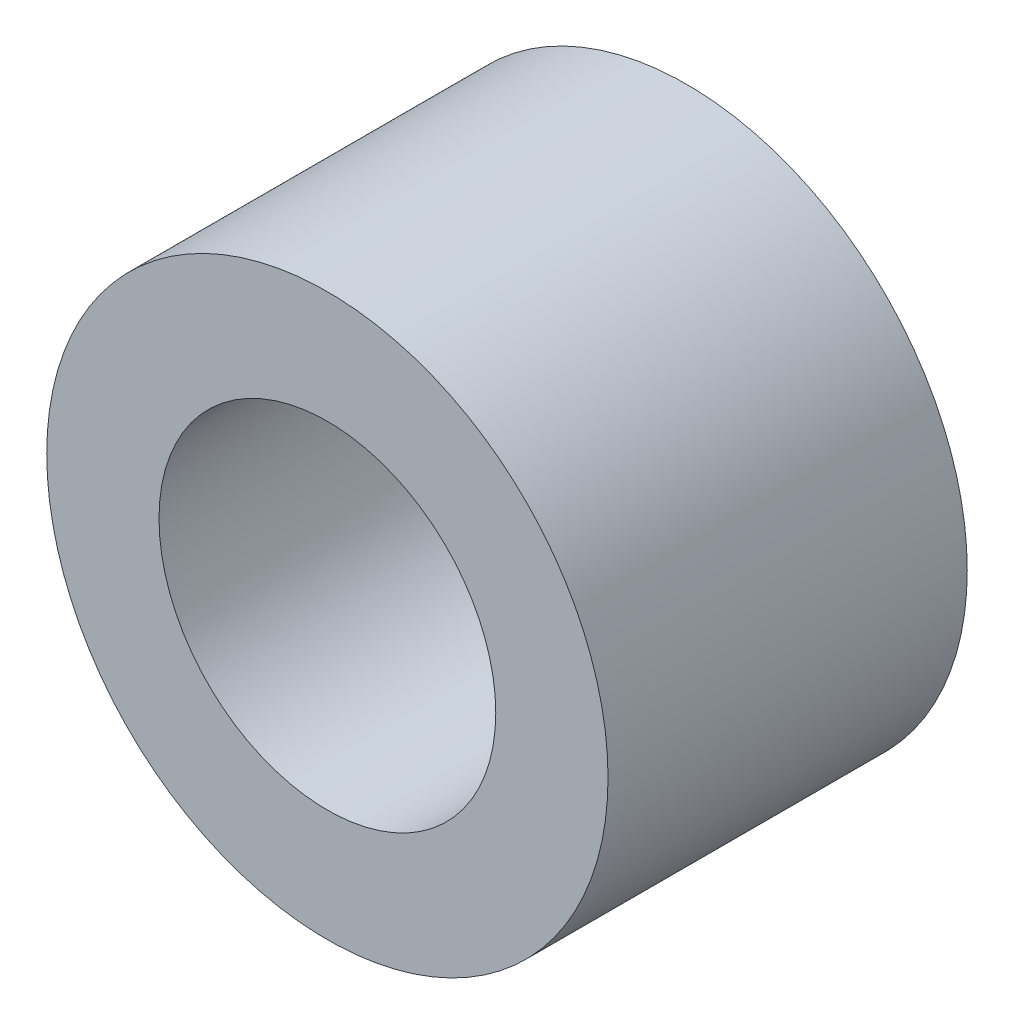
SolidWorks part; units mm, degrees
material "ABS"
ref_plane "前视基准面" through (0, 0, 0) normal (0, 0, 1) x (1, 0, 0)
ref_plane "上视基准面" through (0, 0, 0) normal (0, 1, 0) x (1, 0, 0)
ref_plane "右视基准面" through (0, 0, 0) normal (1, 0, 0) x (0, 0, -1)
sketch "Sketch1" plane through (0, 0, 0) normal (0, 0, 1) x (1, 0, 0)
  circle A0 centre (0, 0) radius 2.5
  circle A1 centre (0, 0) radius 1.5
  dimension "D1" = 3
  dimension "D2" = 5
extrude "Extrude1" add sketch "Sketch1" along normal blind 3.2
